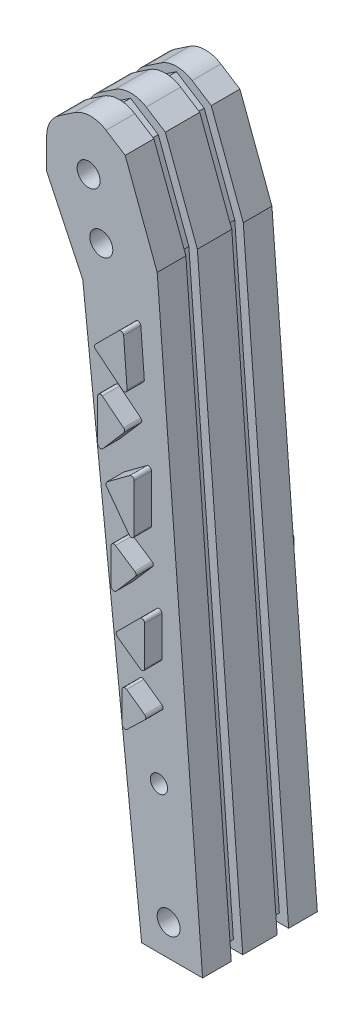
SolidWorks part; units mm, degrees
ref_plane "前视基准面" through (0, 0, 0) normal (0, 0, 1) x (1, 0, 0)
ref_plane "上视基准面" through (0, 0, 0) normal (0, 1, 0) x (1, 0, 0)
ref_plane "右视基准面" through (0, 0, 0) normal (1, 0, 0) x (0, 0, -1)
sketch "草图1" plane through (0, 0, 0) normal (0, 0, 1) x (-1, 0, 0)
  line L1 (74.4382, 158.8017) -> (74.4382, 150.8139)
  line L2 (74.4382, 150.8139) -> (66.8437, 145.6968)
  line L3 (66.8437, 145.6968) -> (60.7541, 149.5814)
  line L12 (55.1748, 164.4598) -> (60.7541, 149.5814)
  line L14 (74.4382, 158.8017) -> (68.1505, 171.9851)
  line L15 (68.1505, 171.9851) -> (57.886, 267.0089)
  line L16 (57.886, 267.0089) -> (47.262, 267.0089)
  line L17 (47.262, 267.0089) -> (55.1748, 164.4598)
extrude "凸台-拉伸1" add sketch "草图1" along normal blind 20
ref_plane "基准面1" through (0, 0, 10) normal (0, 0, -1) x (-1, 0, 0)
sketch "草图113" plane through (0, 0, 10) normal (0, 0, -1) x (-1, 0, 0)
  line L0 (56.654, -164.7873) -> (48.8822, -265.5089)
  line L1 (48.8822, -265.5089) -> (56.5393, -265.5089)
  line L2 (56.5393, -265.5089) -> (66.6867, -171.57)
  line L3 (66.6867, -171.57) -> (72.9382, -158.4623)
  line L4 (72.9382, -158.4623) -> (72.9382, -151.6119)
  line L5 (72.9382, -151.6119) -> (66.8212, -147.4903)
  line L6 (66.8212, -147.4903) -> (61.9828, -150.5768)
  line L7 (61.9828, -150.5768) -> (56.654, -164.7873)
  line L8 (55.1748, -164.4598) -> (47.262, -267.0089)
  line L9 (47.262, -267.0089) -> (57.886, -267.0089)
  line L10 (57.886, -267.0089) -> (68.1505, -171.9851)
  line L11 (68.1505, -171.9851) -> (74.4382, -158.8017)
  line L12 (74.4382, -158.8017) -> (74.4382, -150.8139)
  line L13 (74.4382, -150.8139) -> (66.8437, -145.6968)
  line L14 (66.8437, -145.6968) -> (60.7541, -149.5814)
  line L15 (60.7541, -149.5814) -> (55.1748, -164.4598)
  line L16 (55.1748, -164.4598) -> (47.262, -267.0089)
  line L17 (47.262, -267.0089) -> (57.886, -267.0089)
  line L18 (57.886, -267.0089) -> (68.1505, -171.9851)
  line L19 (68.1505, -171.9851) -> (74.4382, -158.8017)
  line L20 (74.4382, -158.8017) -> (74.4382, -150.8139)
  line L21 (74.4382, -150.8139) -> (66.8437, -145.6968)
  line L22 (66.8437, -145.6968) -> (60.7541, -149.5814)
  line L23 (60.7541, -149.5814) -> (55.1748, -164.4598)
  dimension "D1" = 0
  dimension "D2" = 1.5
extrude "切除-拉伸1" cut sketch "草图113" along normal blind 2 from offset 3
mirror "镜向1" about plane through (0, 0, 10) normal (0, 0, -1) of "切除-拉伸1"
sketch "草图114" plane through (0, 0, 0) normal (0, 0, -1) x (-1, 0, 0)
  line L3 (58.0256, -173.9357) -> (57.4193, -181.7931)
  line L4 (62.9641, -177.707) -> (58.8777, -173.6206)
  line L5 (58.2311, -182.2213) -> (62.9237, -178.4503)
  line L6 (58.0256, -173.9357) -> (57.4193, -181.7931)
  line L7 (62.9641, -177.707) -> (58.8777, -173.6206)
  line L8 (58.2311, -182.2213) -> (62.9237, -178.4503)
  line L9 (60.934, -197.455) -> (56.9712, -194.5186)
  line L10 (56.1735, -194.9204) -> (56.1735, -203.2049)
  line L11 (57.0753, -203.5025) -> (61.0381, -198.1544)
  line L12 (60.934, -197.455) -> (56.9712, -194.5186)
  line L13 (56.1735, -194.9204) -> (56.1735, -203.2049)
  line L14 (57.0753, -203.5025) -> (61.0381, -198.1544)
  line L15 (57.9789, -188.5634) -> (61.6608, -192.8088)
  line L16 (61.7254, -184.8873) -> (58.0434, -187.8461)
  line L17 (62.5386, -192.4812) -> (62.5386, -185.277)
  line L18 (57.9789, -188.5634) -> (61.6608, -192.8088)
  line L19 (61.7254, -184.8873) -> (58.0434, -187.8461)
  line L20 (62.5386, -192.4812) -> (62.5386, -185.277)
  line L21 (59.4429, -206.3138) -> (56.0818, -208.5399)
  line L22 (55.9801, -209.2844) -> (59.3412, -213.1599)
  line L23 (60.219, -212.8323) -> (60.219, -206.7307)
  line L24 (59.4429, -206.3138) -> (56.0818, -208.5399)
  line L25 (55.9801, -209.2844) -> (59.3412, -213.1599)
  line L42 (60.219, -212.8323) -> (60.219, -206.7307)
  line L43 (59.1808, -219.1629) -> (55.2021, -215.1842)
  line L44 (54.3486, -215.5378) -> (54.3486, -222.3661)
  line L45 (55.1397, -222.7726) -> (59.1184, -219.9229)
  line L46 (59.1808, -219.1629) -> (55.2021, -215.1842)
  line L47 (54.3486, -215.5378) -> (54.3486, -222.3661)
  line L48 (55.1397, -222.7726) -> (59.1184, -219.9229)
  line L49 (57.4969, -227.0578) -> (54.3665, -229.3)
  line L50 (54.3107, -230.0665) -> (57.4412, -233.0824)
  line L51 (58.2881, -232.7223) -> (58.2881, -227.4642)
  line L52 (57.4969, -227.0578) -> (54.3665, -229.3)
  line L53 (54.3107, -230.0665) -> (57.4412, -233.0824)
  line L54 (58.2881, -232.7223) -> (58.2881, -227.4642)
  arc A9 (58.8777, -173.6206) -> (58.0256, -173.9357) centre (58.5241, -173.9742) ccw
  arc A10 (62.9237, -178.4503) -> (62.9641, -177.707) centre (62.6105, -178.0606) ccw
  arc A11 (57.4193, -181.7931) -> (58.2311, -182.2213) centre (57.9179, -181.8316) ccw
  arc A12 (58.8777, -173.6206) -> (58.0256, -173.9357) centre (58.5241, -173.9742) ccw
  arc A13 (62.9237, -178.4503) -> (62.9641, -177.707) centre (62.6105, -178.0606) ccw
  arc A14 (57.4193, -181.7931) -> (58.2311, -182.2213) centre (57.9179, -181.8316) ccw
  arc A15 (56.9712, -194.5186) -> (56.1735, -194.9204) centre (56.6735, -194.9204) ccw
  arc A16 (56.1735, -203.2049) -> (57.0753, -203.5025) centre (56.6735, -203.2049) ccw
  arc A17 (61.0381, -198.1544) -> (60.934, -197.455) centre (60.6363, -197.8567) ccw
  arc A18 (56.9712, -194.5186) -> (56.1735, -194.9204) centre (56.6735, -194.9204) ccw
  arc A19 (56.1735, -203.2049) -> (57.0753, -203.5025) centre (56.6735, -203.2049) ccw
  arc A20 (61.0381, -198.1544) -> (60.934, -197.455) centre (60.6363, -197.8567) ccw
  arc A21 (61.6608, -192.8088) -> (62.5386, -192.4812) centre (62.0386, -192.4812) ccw
  arc A22 (58.0434, -187.8461) -> (57.9789, -188.5634) centre (58.3566, -188.2358) ccw
  arc A23 (62.5386, -185.277) -> (61.7254, -184.8873) centre (62.0386, -185.277) ccw
  arc A24 (61.6608, -192.8088) -> (62.5386, -192.4812) centre (62.0386, -192.4812) ccw
  arc A25 (58.0434, -187.8461) -> (57.9789, -188.5634) centre (58.3566, -188.2358) ccw
  arc A26 (62.5386, -185.277) -> (61.7254, -184.8873) centre (62.0386, -185.277) ccw
  arc A27 (56.0818, -208.5399) -> (55.9801, -209.2844) centre (56.3578, -208.9568) ccw
  arc A28 (59.3412, -213.1599) -> (60.219, -212.8323) centre (59.719, -212.8323) ccw
  arc A29 (60.219, -206.7307) -> (59.4429, -206.3138) centre (59.719, -206.7307) ccw
  arc A30 (56.0818, -208.5399) -> (55.9801, -209.2844) centre (56.3578, -208.9568) ccw
  arc A31 (59.3412, -213.1599) -> (60.219, -212.8323) centre (59.719, -212.8323) ccw
  arc A32 (60.219, -206.7307) -> (59.4429, -206.3138) centre (59.719, -206.7307) ccw
  arc A33 (55.2021, -215.1842) -> (54.3486, -215.5378) centre (54.8486, -215.5378) ccw
  arc A34 (54.3486, -222.3661) -> (55.1397, -222.7726) centre (54.8486, -222.3661) ccw
  arc A35 (59.1184, -219.9229) -> (59.1808, -219.1629) centre (58.8272, -219.5164) ccw
  arc A36 (55.2021, -215.1842) -> (54.3486, -215.5378) centre (54.8486, -215.5378) ccw
  arc A37 (54.3486, -222.3661) -> (55.1397, -222.7726) centre (54.8486, -222.3661) ccw
  arc A38 (59.1184, -219.9229) -> (59.1808, -219.1629) centre (58.8272, -219.5164) ccw
  arc A39 (54.3665, -229.3) -> (54.3107, -230.0665) centre (54.6576, -229.7065) ccw
  arc A40 (57.4412, -233.0824) -> (58.2881, -232.7223) centre (57.7881, -232.7223) ccw
  arc A41 (58.2881, -227.4642) -> (57.4969, -227.0578) centre (57.7881, -227.4642) ccw
  arc A42 (54.3665, -229.3) -> (54.3107, -230.0665) centre (54.6576, -229.7065) ccw
  arc A43 (57.4412, -233.0824) -> (58.2881, -232.7223) centre (57.7881, -232.7223) ccw
  arc A44 (58.2881, -227.4642) -> (57.4969, -227.0578) centre (57.7881, -227.4642) ccw
  dimension "D4" = 0
  dimension "D5" = 0
  dimension "D6" = 0
  dimension "D8" = 0
  dimension "D9" = 0
  dimension "D10" = 0
extrude "凸台-拉伸2" add sketch "草图114" along normal blind 3
ref_plane "基准面2" through (0, 0, 10) normal (0, 0, -1) x (-1, 0, 0)
mirror "镜向2" about plane through (0, 0, 10) normal (0, 0, -1) of "凸台-拉伸2"
sketch "草图115" plane through (0, 0, 0) normal (0, 0, -1) x (-1, 0, 0)
  circle A1 centre (64.9158, -164.9498) radius 2
  circle A2 centre (64.9158, -164.9498) radius 2
  circle A3 centre (67.1321, -155.6447) radius 2
  circle A4 centre (67.1321, -155.6447) radius 2
  circle A5 centre (54.8672, -241.4894) radius 1.5
  circle A6 centre (54.8672, -241.4894) radius 1.5
  dimension "D1" = 0
  dimension "D2" = 0
  dimension "D3" = 0
extrude "切除-拉伸2" cut sketch "草图115" against normal through all
fillet "圆角1" radius 5 6 edges at (-66.8437, -145.6968, 17.5) (-66.8437, -145.6968, 10) (-74.4382, -150.8139, 17.5) (-74.4382, -150.8139, 10) (-74.4382, -150.8139, 2.5) (-66.8437, -145.6968, 2.5)
sketch "草图116" plane through (0, 0, 0) normal (0, 0, -1) x (-1, 0, 0)
  circle A0 centre (53.1848, -261.5584) radius 2 construction
  circle A1 centre (53.1848, -261.5584) radius 2
extrude "切除-拉伸3" cut sketch "草图116" against normal through all
